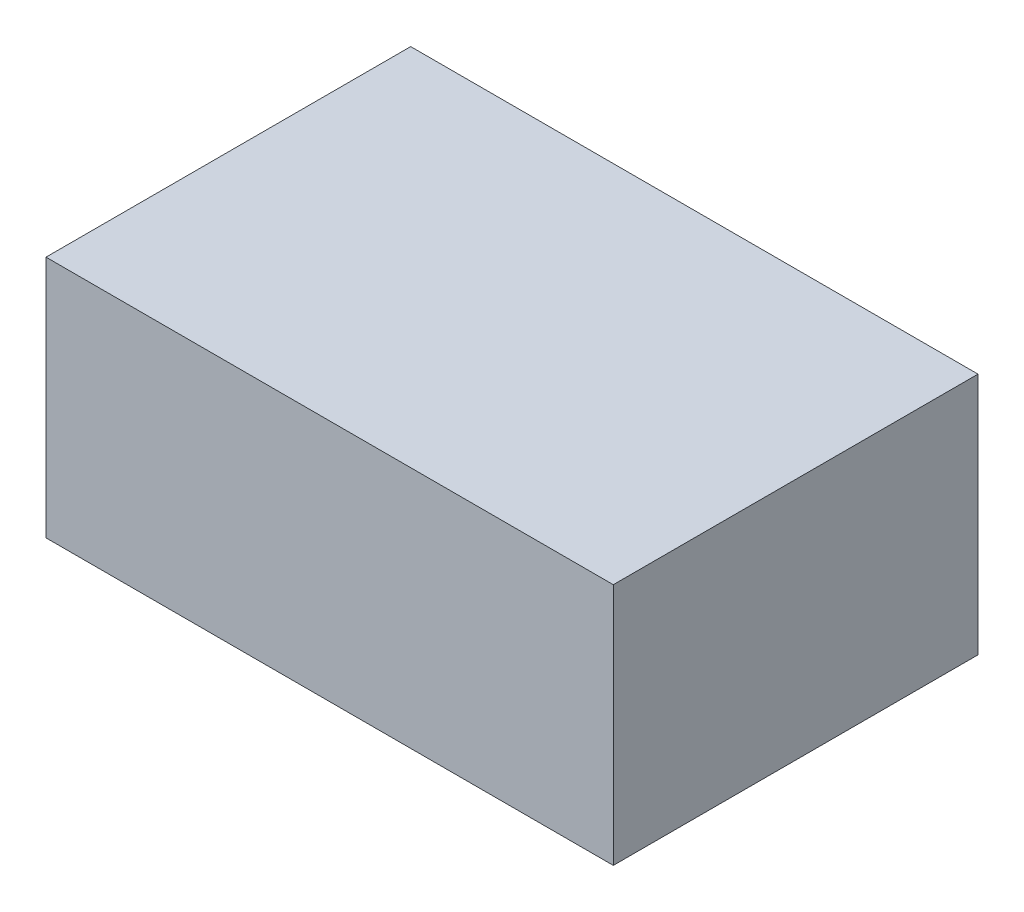
SolidWorks part; units mm, degrees
ref_plane "Front Plane" through (0, 0, 0) normal (0, 0, 1) x (1, 0, 0)
ref_plane "Top Plane" through (0, 0, 0) normal (0, 1, 0) x (1, 0, 0)
ref_plane "Right Plane" through (0, 0, 0) normal (1, 0, 0) x (0, 0, -1)
sketch "Sketch1" plane through (0, 0, 0) normal (0, 1, 0) x (1, 0, 0)
  line L1 (0, 0) -> (71.12, 0)
  line L2 (0, 0) -> (0, 45.72)
  line L3 (0, 45.72) -> (71.12, 45.72)
  line L4 (71.12, 0) -> (71.12, 45.72)
  dimension "D1" = 71.12
  dimension "D2" = 45.72
extrude "Boss-Extrude1" add sketch "Sketch1" along normal blind 30.48
